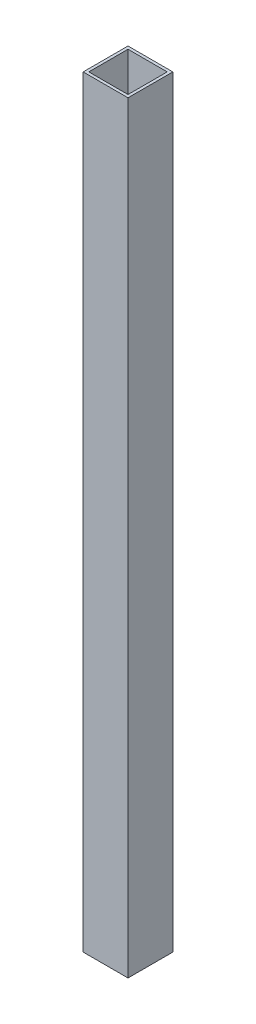
SolidWorks part; units mm, degrees
material "6061 Alloy"
ref_plane "Front Plane" through (0, 0, 0) normal (0, 0, 1) x (1, 0, 0)
ref_plane "Top Plane" through (0, 0, 0) normal (0, 1, 0) x (1, 0, 0)
ref_plane "Right Plane" through (0, 0, 0) normal (1, 0, 0) x (0, 0, -1)
sketch "Sketch1" plane through (0, 0, 0) normal (0, 1, 0) x (1, 0, 0)
  line L1 (-12.7, -12.7) -> (12.7, -12.7)
  line L2 (-12.7, -12.7) -> (-12.7, 12.7)
  line L3 (-12.7, 12.7) -> (12.7, 12.7)
  line L4 (12.7, -12.7) -> (12.7, 12.7)
  line L7 (-11.1125, -11.1125) -> (11.1125, -11.1125)
  line L8 (-11.1125, -11.1125) -> (-11.1125, 11.1125)
  line L9 (-11.1125, 11.1125) -> (11.1125, 11.1125)
  line L10 (11.1125, -11.1125) -> (11.1125, 11.1125)
  point P6 (0, 0)
  dimension "D1" = 25.4
  dimension "D2" = 25.4
  dimension "D3" = 1.5875
  dimension "D4" = 1.5875
  dimension "D5" = 1.5875
extrude "Boss-Extrude1" add sketch "Sketch1" along normal blind 431.8
